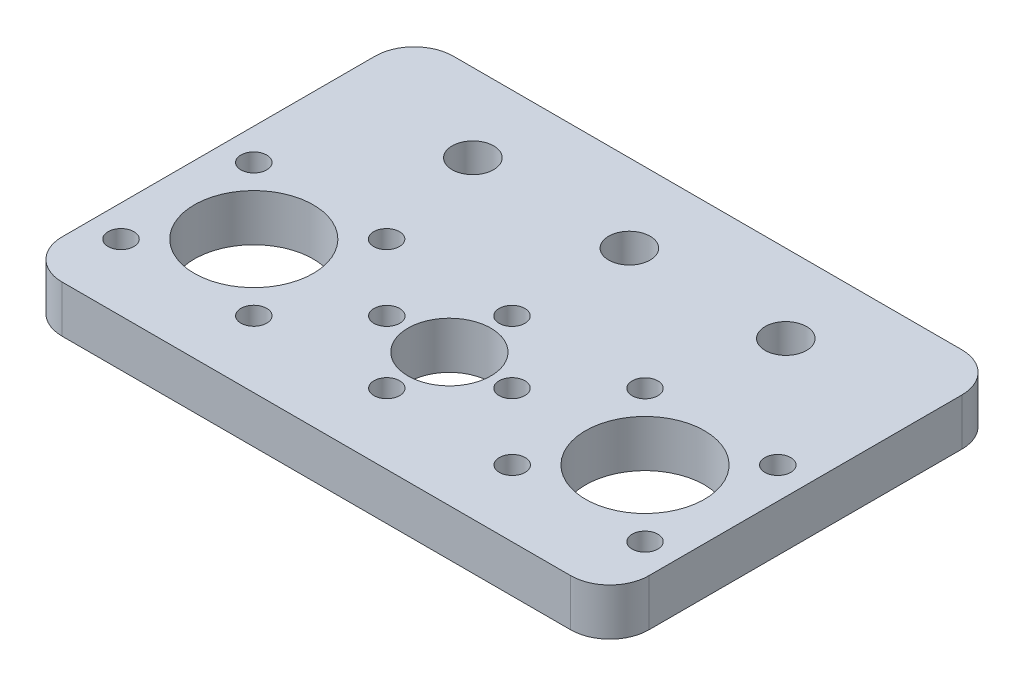
SolidWorks part; units mm, degrees
ref_plane "前视基准面" through (0, 0, 0) normal (0, 0, 1) x (1, 0, 0)
ref_plane "上视基准面" through (0, 0, 0) normal (0, 1, 0) x (1, 0, 0)
ref_plane "右视基准面" through (0, 0, 0) normal (1, 0, 0) x (0, 0, -1)
other "Configuration Table"
sketch "草图1" plane through (0, 0, 0) normal (0, 1, 0) x (1, 0, 0)
  line L0 (0, 71.581) -> (0, -69.303) construction
  line L1 (-102.6841, 0) -> (111.095, 0) construction
  line L2 (-25, 71.581) -> (-25, -69.303) construction
  line L3 (25, 71.581) -> (25, -69.303) construction
  line L4 (-33.4853, 8.4853) -> (-16.5147, 8.4853) construction
  line L5 (-37.5, 28) -> (-37.5, -12)
  line L6 (37.5, 28) -> (37.5, -12)
  line L7 (-32.5, -17) -> (32.5, -17)
  line L8 (-102.6841, 13) -> (111.095, 13) construction
  line L9 (-102.6841, 23) -> (111.095, 23) construction
  line L10 (-20, 71.581) -> (-20, -69.303) construction
  line L11 (20, 71.581) -> (20, -69.303) construction
  line L12 (-32.5, 33) -> (32.5, 33)
  line L13 (-37.5, 71.581) -> (-37.5, -69.303) construction
  line L14 (-102.6841, -17) -> (111.095, -17) construction
  line L15 (37.5, 71.581) -> (37.5, -69.303) construction
  line L16 (-102.6841, 33) -> (111.095, 33) construction
  circle A0 centre (-25, 0) radius 7.6
  circle A1 centre (-25, 0) radius 12 construction
  circle A2 centre (-33.4853, 8.4853) radius 1.65
  circle A3 centre (-16.5147, 8.4853) radius 1.65
  circle A4 centre (-16.5147, -8.4853) radius 1.65
  circle A5 centre (-33.4853, -8.4853) radius 1.65
  circle A6 centre (33.4853, -8.4853) radius 1.65
  circle A7 centre (16.5147, -8.4853) radius 1.65
  circle A8 centre (16.5147, 8.4853) radius 1.65
  circle A9 centre (33.4853, 8.4853) radius 1.65
  circle A10 centre (25, 0) radius 7.6
  circle A11 centre (0, 0) radius 5.3
  circle A12 centre (0, 0) radius 8 construction
  circle A13 centre (0, 8) radius 1.65
  circle A14 centre (8, 0) radius 1.65
  circle A15 centre (0, -8) radius 1.65
  circle A16 centre (-8, 0) radius 1.65
  circle A17 centre (-20, 23) radius 2.65
  circle A18 centre (0, 23) radius 2.65
  circle A19 centre (20, 23) radius 2.65
  arc A20 (-37.5, -12) -> (-32.5, -17) centre (-32.5, -12) ccw
  arc A21 (32.5, -17) -> (37.5, -12) centre (32.5, -12) ccw
  arc A22 (37.5, 28) -> (32.5, 33) centre (32.5, 28) ccw
  arc A23 (-32.5, 33) -> (-37.5, 28) centre (-32.5, 28) ccw
  point P23 (-25, 0)
  point P31 (25, 0)
  point P50 (0, 0)
  dimension "D3" = 15.2
  dimension "D4" = 24
  dimension "D5" = 3.3
  dimension "D9" = 10.6
  dimension "D10" = 16
  dimension "D11" = 3.3
  dimension "D18" = 5.3
  dimension "D21" = 5
  dimension "D1" = 25
  dimension "D7" = 12.5
  dimension "D2" = 25
  dimension "D8" = 12.5
  dimension "D13" = 17
  dimension "D14" = 13
  dimension "D15" = 10
  dimension "D16" = 20
  dimension "D17" = 20
  dimension "D20" = 10
  dimension "D19" = 3
  dimension "D6" = 4
  dimension "D12" = 4
extrude "凸台-拉伸1" add sketch "草图1" along normal blind 6
sketch "草图2" plane through (0, 0, 0) normal (0, 1, 0) x (1, 0, 0)
  line L0 (21.7416, -15.1788) -> (29.7379, -15.1788) construction
  text T0 "<b>wxy</b>"
extrude "凸台-拉伸2" add sketch "草图2" against normal blind 1
